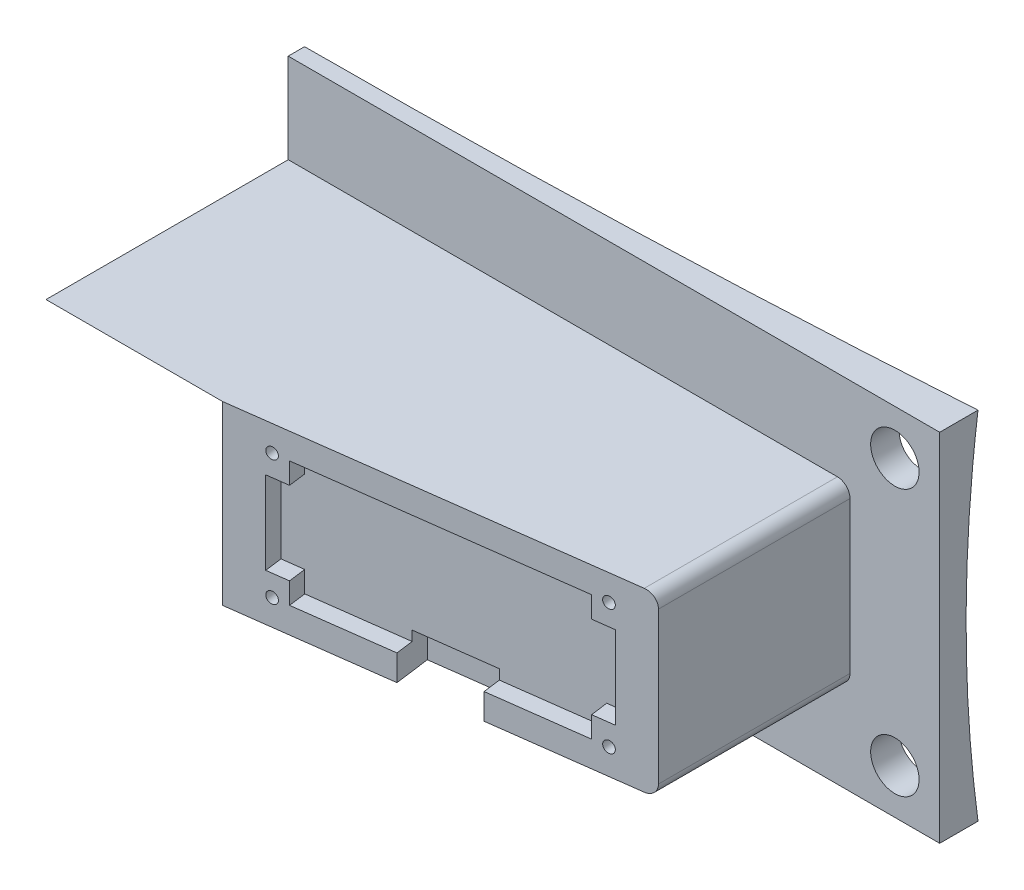
SolidWorks part; units mm, degrees
material "Nylon 101"
ref_plane "Front Plane" through (0, 0, 0) normal (0, 0, 1) x (1, 0, 0)
ref_plane "Top Plane" through (0, 0, 0) normal (0, 1, 0) x (1, 0, 0)
ref_plane "Right Plane" through (0, 0, 0) normal (1, 0, 0) x (0, 0, -1)
sketch "Sketch6" plane through (0, 0, 0) normal (0, 1, 0) x (1, 0, 0)
  line L6 (-79.5295, 0) -> (79.5295, 0)
  line L7 (-79.5295, 0) -> (-79.5295, -56.3211)
  line L8 (-79.5295, -56.3211) -> (-25, -63.5)
  line L9 (-25, -63.5) -> (25, -63.5)
  line L10 (25, -63.5) -> (79.5295, -56.3211)
  line L11 (79.5295, -56.3211) -> (79.5295, 0)
  line L12 (0, -63.5) -> (0, 0) construction
  point P4 (0, 0)
  point P10 (0, -63.5)
  dimension "D1" = 172.5
  dimension "D2" = 55
  dimension "D3" = 63.5
  dimension "D4" = 50
extrude "Boss-Extrude4" add sketch "Sketch6" along normal blind 25
sketch "Sketch7" plane through (0, 0, 0) normal (1, 0, 0) x (0, 0, -1)
  line L0 (-63.5, 25) -> (-38.5, 0)
  line L1 (-63.5, 0) -> (-56.3211, 0) construction
  line L2 (-63.5, 25) -> (-63.5, 0) construction
  line L3 (-63.5, 25) -> (-63.5, 0)
  line L4 (-63.5, 0) -> (-38.5, 0)
  dimension "D1" = 45
extrude "Cut-Extrude2" cut sketch "Sketch7" against normal mid plane 50
hole_wizard "Tap Drill for #4-40 Tap1" positions "Sketch9" profile "Sketch10" hole size "#4-40" standard "ANSI Inch"
sketch "Sketch9" plane through (0, -19.25, 19.25) normal (0, -0.7071, 0.7071) x (-1, 0, 0)
  line L0 (21.255, -53.7563) -> (21.255, -36.0463) construction
  line L2 (25, -27.2236) -> (25, -62.579) construction
  line L3 (21.255, -53.7563) -> (-21.255, -53.7563) construction
  line L5 (25, -62.579) -> (-25, -62.579) construction
  point P0 (-21.255, -53.7563)
  point P2 (21.255, -53.7563)
  point P4 (21.255, -36.0463)
  point P6 (-21.255, -36.0463)
  point P18 (21.255, -44.9013)
  point P21 (25, -44.9013)
  point P29 (0, -53.7563)
  point P32 (0, -62.579)
  dimension "D1" = 42.51
  dimension "D2" = 17.71
sketch "Sketch10" plane through (21.255, 18.7614, 57.2614) normal (1, 0, 0) x (0, -0.7071, -0.7071)
  line L0 (0, 0) -> (0, 8.3547)
  line L1 (0, 8.3547) -> (0.8, 7.874)
  line L2 (0.8, 7.874) -> (0.8, 0)
  line L5 (0.8, 0) -> (0, 0)
  line L10 (0, 8.3547) -> (-0.8, 7.874) construction
  line L11 (0, -6.35) -> (0, 107.95) construction
  dimension "Hole Dia." = 1.6
  dimension "Hole Depth" = 7.874
  dimension "Drill Angle" = 118
hole_wizard "Tap Drill for #4-40 Tap3" positions "Sketch14" profile "Sketch15" hole size "#4-40" standard "ANSI Inch"
sketch "Sketch14" plane through (-8.6434, 0, 65.6534) normal (-0.1305, 0, 0.9914) x (0.9914, 0, 0.1305)
  line L2 (-22.7427, 21.355) -> (-65.2527, 21.355) construction
  line L3 (-65.2527, 21.355) -> (-65.2527, 3.645) construction
  line L5 (-71.4977, 25) -> (-16.4977, 25) construction
  line L6 (-71.4977, 25) -> (-71.4977, 0) construction
  point P0 (-65.2527, 21.355)
  point P12 (-22.7427, 21.355)
  point P13 (-22.7427, 3.645)
  point P14 (-65.2527, 3.645)
  point P26 (-43.9977, 21.355)
  point P29 (-43.9977, 25)
  point P30 (-65.2527, 12.5)
  point P33 (-71.4977, 12.5)
  dimension "D3" = 42.51
  dimension "D4" = 17.71
  dimension "D1" = 2
  dimension "D2" = 2
sketch "Sketch15" plane through (-73.3379, 21.355, 57.1362) normal (0, 1, 0) x (0.9914, 0, 0.1305)
  line L0 (0, 0) -> (0, 8.3547)
  line L1 (0, 8.3547) -> (0.8, 7.874)
  line L2 (0.8, 7.874) -> (0.8, 0)
  line L5 (0.8, 0) -> (0, 0)
  line L10 (0, 8.3547) -> (-0.8, 7.874) construction
  line L11 (0, -6.35) -> (0, 107.95) construction
  dimension "Hole Dia." = 1.6
  dimension "Hole Depth" = 7.874
  dimension "Drill Angle" = 118
hole_wizard "Tap Drill for #4-40 Tap4" positions "Sketch18" profile "Sketch19" hole size "#4-40" standard "ANSI Inch"
sketch "Sketch18" plane through (8.6434, 0, 65.6534) normal (0.1305, 0, 0.9914) x (0.9914, 0, -0.1305)
  line L2 (22.7427, 3.645) -> (22.7427, 21.355) construction
  line L3 (22.7427, 21.355) -> (65.2527, 21.355) construction
  line L6 (16.4977, 25) -> (71.4977, 25) construction
  line L7 (16.4977, 25) -> (16.4977, 0) construction
  point P0 (22.7427, 21.355)
  point P9 (65.2527, 21.355)
  point P10 (65.2527, 3.645)
  point P11 (22.7427, 3.645)
  point P22 (43.9977, 21.355)
  point P25 (43.9977, 25)
  point P26 (22.7427, 12.5)
  point P29 (16.4977, 12.5)
  dimension "D3" = 42.51
  dimension "D4" = 17.71
  dimension "D1" = 2
  dimension "D2" = 2
sketch "Sketch19" plane through (31.1916, 21.355, 62.6849) normal (0, 1, 0) x (0.9914, 0, -0.1305)
  line L0 (0, 0) -> (0, 8.3547)
  line L1 (0, 8.3547) -> (0.8, 7.874)
  line L2 (0.8, 7.874) -> (0.8, 0)
  line L5 (0.8, 0) -> (0, 0)
  line L10 (0, 8.3547) -> (-0.8, 7.874) construction
  line L11 (0, -6.35) -> (0, 107.95) construction
  dimension "Hole Dia." = 1.6
  dimension "Hole Depth" = 7.874
  dimension "Drill Angle" = 118
fillet "Fillet1" radius 1.778 4 edges at (79.5295, 25, 28.1605) (79.5295, 0, 28.1605) (-79.5295, 0, 28.1605) (-79.5295, 25, 28.1605)
sketch "Sketch20" plane through (-8.6434, 0, 65.6534) normal (-0.1305, 0, 0.9914) x (0.9914, 0, 0.1305)
  line L0 (-63.0527, 21.355) -> (-63.0527, 18.355)
  line L1 (-63.0527, 18.355) -> (-66.0527, 18.355)
  line L2 (-66.0527, 18.355) -> (-66.0527, 6.645)
  line L3 (-66.0527, 6.645) -> (-63.0527, 6.645)
  line L4 (-63.0527, 6.645) -> (-63.0527, 3.645)
  line L5 (-63.0527, 3.645) -> (-24.9427, 3.645)
  line L6 (-24.9427, 3.645) -> (-24.9427, 6.645)
  line L7 (-24.9427, 6.645) -> (-21.9427, 6.645)
  line L8 (-21.9427, 6.645) -> (-21.9427, 18.355)
  line L9 (-21.9427, 18.355) -> (-24.9427, 18.355)
  line L10 (-24.9427, 18.355) -> (-24.9427, 21.355)
  line L11 (-24.9427, 21.355) -> (-63.0527, 21.355)
  circle A2 centre (-65.2527, 21.355) radius 0.8 construction
  circle A3 centre (-65.2527, 21.355) radius 0.8 construction
  circle A4 centre (-22.7427, 21.355) radius 0.8 construction
  point P11 (-66.0527, 21.355)
  point P14 (-21.9427, 21.355)
  dimension "D1" = 3
  dimension "D2" = 3
sketch "Sketch21" plane through (8.6434, 0, 65.6534) normal (0.1305, 0, 0.9914) x (0.9914, 0, -0.1305)
  line L0 (24.9427, 21.355) -> (24.9427, 18.355)
  line L1 (24.9427, 18.355) -> (21.9427, 18.355)
  line L2 (21.9427, 18.355) -> (21.9427, 6.645)
  line L3 (21.9427, 6.645) -> (24.9427, 6.645)
  line L4 (24.9427, 6.645) -> (24.9427, 3.645)
  line L5 (24.9427, 3.645) -> (63.0527, 3.645)
  line L6 (63.0527, 3.645) -> (63.0527, 6.645)
  line L7 (63.0527, 6.645) -> (66.0527, 6.645)
  line L8 (66.0527, 6.645) -> (66.0527, 18.355)
  line L9 (66.0527, 18.355) -> (63.0527, 18.355)
  line L10 (63.0527, 18.355) -> (63.0527, 21.355)
  line L11 (63.0527, 21.355) -> (24.9427, 21.355)
  circle A0 centre (22.7427, 21.355) radius 0.8 construction
  circle A1 centre (22.7427, 21.355) radius 0.8 construction
  circle A2 centre (65.2527, 21.355) radius 0.8 construction
  circle A3 centre (65.2527, 21.355) radius 0.8 construction
  point P11 (21.9427, 21.355)
  point P14 (66.0527, 21.355)
  dimension "D1" = 3
  dimension "D2" = 3
sketch "Sketch22" plane through (0, -19.25, 19.25) normal (0, -0.7071, 0.7071) x (1, 0, 0)
  line L0 (-19.055, 53.7563) -> (-19.055, 50.7563)
  line L1 (-19.055, 50.7563) -> (-22.055, 50.7563)
  line L2 (-22.055, 50.7563) -> (-22.055, 39.0463)
  line L3 (-22.055, 39.0463) -> (-19.055, 39.0463)
  line L4 (-19.055, 39.0463) -> (-19.055, 36.0463)
  line L5 (-19.055, 36.0463) -> (19.055, 36.0463)
  line L6 (19.055, 36.0463) -> (19.055, 39.0463)
  line L7 (19.055, 39.0463) -> (22.055, 39.0463)
  line L8 (22.055, 39.0463) -> (22.055, 50.7563)
  line L9 (22.055, 50.7563) -> (19.055, 50.7563)
  line L10 (19.055, 50.7563) -> (19.055, 53.7563)
  line L11 (19.055, 53.7563) -> (-19.055, 53.7563)
  circle A0 centre (-21.255, 53.7563) radius 0.8 construction
  circle A1 centre (-21.255, 53.7563) radius 0.8 construction
  circle A2 centre (21.255, 53.7563) radius 0.8 construction
  circle A3 centre (21.255, 53.7563) radius 0.8 construction
  point P18 (22.055, 53.7563)
  point P25 (-22.055, 53.7563)
  dimension "D1" = 3
  dimension "D2" = 3
extrude "Cut-Extrude3" cut sketch "Sketch22" against normal blind 2.5
extrude "Cut-Extrude4" cut sketch "Sketch21" against normal blind 2.5 contours L5 L6 L7 L8 L9 L10 L11 L0 L1 L2 L3 L4
extrude "Cut-Extrude5" cut sketch "Sketch20" against normal blind 2.5 contours L5 L6 L7 L8 L9 L10 L11 L0 L1 L2 L3 L4
sketch "Sketch23" plane through (8.6434, 0, 65.6534) normal (0.1305, 0, 0.9914) x (0.9914, 0, -0.1305)
  line L1 (38.4977, 5.045) -> (49.4977, 5.045)
  line L2 (38.4977, 5.045) -> (38.4977, 0)
  line L3 (38.4977, 0) -> (49.4977, 0)
  line L4 (49.4977, 5.045) -> (49.4977, 0)
  line L5 (24.9427, 3.645) -> (63.0527, 3.645) construction
  line L6 (24.9427, 3.645) -> (63.0527, 3.645) construction
  line L7 (16.4977, 0) -> (69.7044, 0) construction
  point P0 (43.9977, 5.045)
  point P12 (43.9977, 3.645)
  dimension "D1" = 11
  dimension "D2" = 1.4
extrude "Cut-Extrude6" cut sketch "Sketch23" against normal blind 5
sketch "Sketch24" plane through (-8.6434, 0, 65.6534) normal (-0.1305, 0, 0.9914) x (0.9914, 0, 0.1305)
  line L0 (-49.4977, 5.045) -> (-38.4977, 5.045)
  line L1 (-49.4977, 5.045) -> (-49.4977, 0)
  line L2 (-49.4977, 0) -> (-38.4977, 0)
  line L3 (-38.4977, 5.045) -> (-38.4977, 0)
  line L4 (-63.0527, 3.645) -> (-24.9427, 3.645) construction
  line L5 (-69.7044, 0) -> (-16.4977, 0) construction
  point P0 (-43.9977, 5.045)
  point P7 (-43.9977, 3.645)
  dimension "D1" = 11
  dimension "D2" = 1.4
extrude "Cut-Extrude7" cut sketch "Sketch24" against normal blind 5
sketch "Sketch25" plane through (0, -19.25, 19.25) normal (0, -0.7071, 0.7071) x (1, 0, 0)
  line L0 (-5.5, 37.4463) -> (5.5, 37.4463)
  line L1 (-5.5, 37.4463) -> (-5.5, 21.3712)
  line L2 (-5.5, 21.3712) -> (5.5, 21.3712)
  line L3 (5.5, 37.4463) -> (5.5, 21.3712)
  line L4 (-19.055, 36.0463) -> (19.055, 36.0463) construction
  point P0 (0, 37.4463)
  point P7 (0, 36.0463)
  dimension "D1" = 11
  dimension "D2" = 1.4
extrude "Cut-Extrude8" cut sketch "Sketch25" against normal blind 10 contours L3 L2 L1 L0
sketch "Sketch26" plane through (0, 0, 0) normal (0, 0, -1) x (-1, 0, 0)
  line L0 (-77.7515, 25) -> (77.7515, 25) construction
  line L1 (-92.2295, -12.7) -> (92.2295, -12.7)
  line L2 (-92.2295, -12.7) -> (-92.2295, 37.7)
  line L3 (-92.2295, 37.7) -> (92.2295, 37.7)
  line L4 (92.2295, -12.7) -> (92.2295, 37.7)
  line L5 (-92.2295, -12.7) -> (92.2295, 37.7) construction
  line L6 (-92.2295, 37.7) -> (92.2295, -12.7) construction
  line L7 (-79.5295, 23.222) -> (-79.5295, 1.778) construction
  point P0 (0, 12.5)
  point P9 (0, 37.7)
  point P11 (-92.2295, 12.5)
  point P12 (-79.5295, 12.5)
  dimension "D1" = 12.7
  dimension "D2" = 12.7
extrude "Boss-Extrude6" add sketch "Sketch26" against normal blind 29.21
sketch "Sketch11" plane through (0, 0, 0) normal (1, 0, 0) x (0, 0, -1)
  line L0 (-28.575, 12.5) -> (1344.295, 12.5) construction
  line L1 (0, 25) -> (0, 0) construction
  line L2 (1344.295, -496.77) -> (1344.295, 521.77)
  ellipse E0 centre (1344.295, 12.5) end of major axis (-28.575, 12.5) minor radius 509.27 (1344.295, 521.77) -> (1344.295, -496.77) ccw
  point P7 (1344.295, 12.5)
  point P15 (0, 12.5)
  dimension "D1" = 1372.87
  dimension "D2" = 1018.54
  dimension "D3" = 28.575
revolve "Cut-Revolve4" cut sketch "Sketch11" angle 360 about L2
sketch "Sketch27" plane through (0, 0, 29.21) normal (0, 0, 1) x (1, 0, 0)
  line L0 (92.2295, 37.7) -> (92.2295, -12.7) construction
  line L1 (92.2295, -12.7) -> (-92.2295, -12.7) construction
  line L2 (-92.2295, 37.7) -> (92.2295, 37.7) construction
  line L3 (-92.2295, -12.7) -> (-92.2295, 37.7) construction
  circle A0 centre (85.8795, -6.35) radius 3.429
  circle A1 centre (-85.8795, -6.35) radius 3.429
  circle A2 centre (-85.8795, 31.35) radius 3.429
  circle A3 centre (85.8795, 31.35) radius 3.429
  dimension "D1" = 6.858
  dimension "D2" = 6.35
  dimension "D6" = 6.35
  dimension "D7" = 6.35
  dimension "D3" = 6.35
  dimension "D4" = 2
  dimension "D5" = 2
extrude "Cut-Extrude9" cut sketch "Sketch27" against normal through all
sketch "Sketch28" plane through (0, 0, 0) normal (1, 0, 0) x (0, 0, -1)
  line L1 (-128.5879, -72.1569) -> (-12.6705, -72.1569)
  line L2 (-128.5879, -72.1569) -> (-128.5879, 40.0336)
  line L3 (-128.5879, 40.0336) -> (-12.6705, 40.0336)
  line L4 (-12.6705, -72.1569) -> (-12.6705, 40.0336)
  line L5 (-128.5879, -72.1569) -> (-12.6705, 40.0336) construction
  line L6 (-128.5879, 40.0336) -> (-12.6705, -72.1569) construction
  point P0 (-70.6292, -16.0617)
extrude "Cut-Extrude10" cut sketch "Sketch28" against normal through all contours L2 L3 L4 L1
